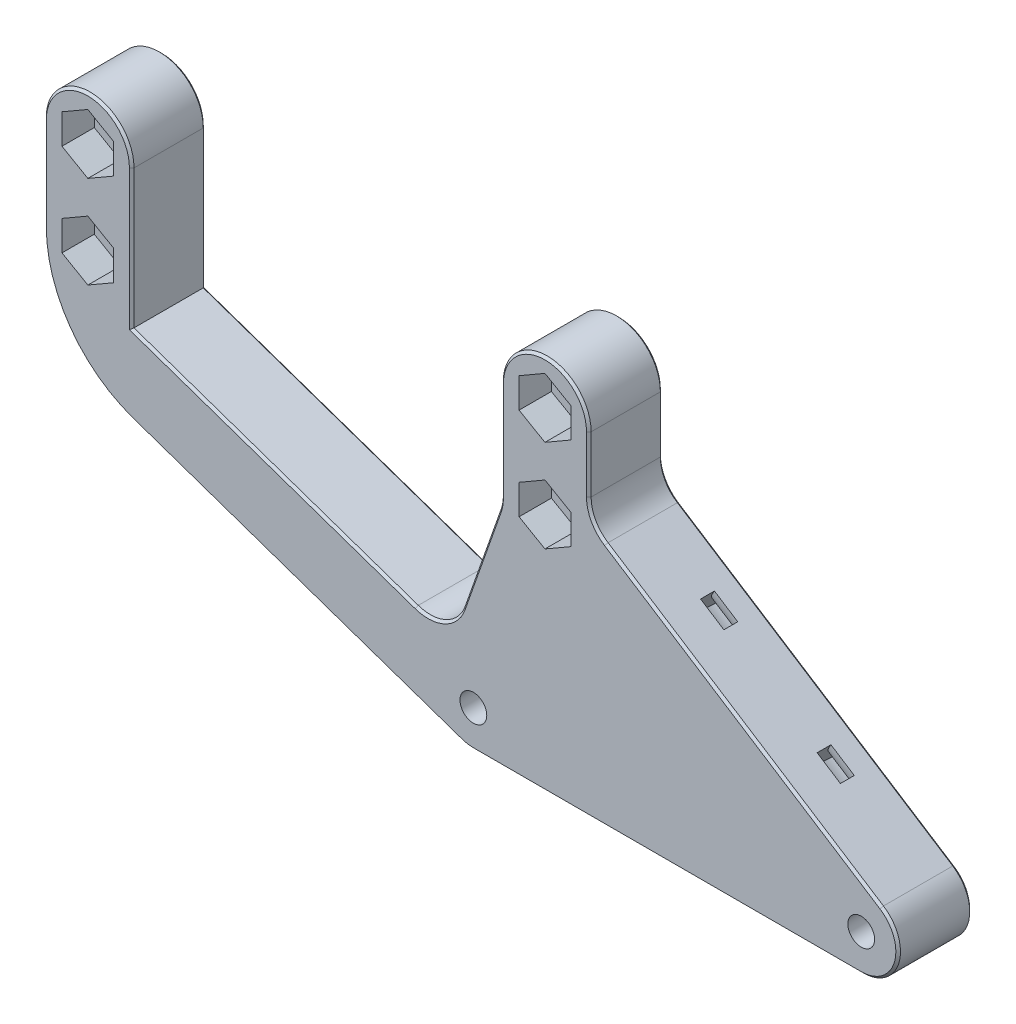
SolidWorks part; units mm, degrees
ref_plane "Płaszczyzna przednia" through (0, 0, 0) normal (0, 0, 1) x (1, 0, 0)
ref_plane "Płaszczyzna górna" through (0, 0, 0) normal (0, 1, 0) x (1, 0, 0)
ref_plane "Płaszczyzna prawa" through (0, 0, 0) normal (1, 0, 0) x (0, 0, -1)
sketch "Szkic1" plane through (0, 0, 0) normal (0, 0, 1) x (1, 0, 0)
  line L0 (0, 0) -> (7, -27) construction
  line L1 (7, -27) -> (49, -27) construction
  line L2 (0, 0) -> (-10, 0) construction
  line L3 (-34.75, 5) -> (14.75, 5) construction
  line L4 (-34.75, 5) -> (-34.75, -5) construction
  line L5 (-34.75, -5) -> (14.75, -5) construction
  line L6 (14.75, 5) -> (14.75, -5) construction
  line L7 (-34.75, 5) -> (14.75, -5) construction
  line L8 (-34.75, -5) -> (14.75, 5) construction
  line L9 (-34.75, 5) -> (-34.75, -5) construction
  line L10 (-30, 5) -> (-30, -5)
  line L11 (-39.5, 5) -> (-39.5, -5)
  line L12 (14.75, 5) -> (14.75, -5) construction
  line L13 (19.5, 5) -> (19.5, -5)
  line L14 (10, 5) -> (10, -5)
  line L15 (7, -27) -> (49, -27) construction
  line L16 (7, -27) -> (14.75, -5) construction
  line L17 (14.75, -5) -> (49, -27) construction
  line L18 (7, -23) -> (49, -23)
  line L19 (7, -31) -> (49, -31)
  line L20 (49, -27) -> (14.75, -5) construction
  line L21 (46.8382, -30.3655) -> (12.5882, -8.3655)
  line L22 (51.1618, -23.6345) -> (16.9118, -1.6345)
  line L23 (14.75, -5) -> (7, -27) construction
  line L24 (18.5228, -6.329) -> (10.7728, -28.329)
  line L25 (10.9772, -3.671) -> (3.2272, -25.671)
  line L26 (10, -5) -> (10, -6.4451)
  line L27 (7, -27) -> (-28.5677, -14.7258) construction
  line L28 (5.6951, -30.7812) -> (-29.8726, -18.5069)
  line L29 (8.3049, -23.2188) -> (-27.2628, -10.9446)
  line L30 (-30, -5) -> (-30, -10)
  line L31 (-27.2628, -10.9446) -> (-30, -10)
  circle A0 centre (7, -27) radius 1.45
  circle A1 centre (49, -27) radius 1.45
  circle A2 centre (14.75, -5) radius 1.55
  circle A3 centre (14.75, 5) radius 1.55
  circle A4 centre (-34.75, 5) radius 1.55
  circle A5 centre (-34.75, -5) radius 1.55
  arc A6 (-30, 5) -> (-39.5, 5) centre (-34.75, 5) ccw
  arc A7 (-39.5, -5) -> (-30, -5) centre (-34.75, -5) ccw
  arc A8 (19.5, 5) -> (10, 5) centre (14.75, 5) ccw
  arc A9 (10, -5) -> (19.5, -5) centre (14.75, -5) ccw
  arc A10 (7, -23) -> (7, -31) centre (7, -27) ccw
  arc A11 (49, -31) -> (49, -23) centre (49, -27) ccw
  arc A12 (46.8382, -30.3655) -> (51.1618, -23.6345) centre (49, -27) ccw
  arc A13 (16.9118, -1.6345) -> (12.5882, -8.3655) centre (14.75, -5) ccw
  arc A14 (18.5228, -6.329) -> (10.9772, -3.671) centre (14.75, -5) ccw
  arc A15 (3.2272, -25.671) -> (10.7728, -28.329) centre (7, -27) ccw
  arc A16 (5.6951, -30.7812) -> (8.3049, -23.2188) centre (7, -27) ccw
  arc A17 (-27.2628, -10.9446) -> (-29.8726, -18.5069) centre (-28.5677, -14.7258) ccw
  arc A18 (-39.5, -5) -> (-29.8726, -18.5069) centre (-25.2114, -5) ccw
  point P3 (-10, 0)
  point P16 (-34.75, 0)
  point P21 (14.75, 0)
  point P26 (28, -27)
  point P32 (31.875, -16)
  point P38 (10.875, -16)
  point P49 (-10.7839, -20.8629)
  dimension "D7" = 3.1
  dimension "D8" = 2.9
  dimension "D10" = 4
  dimension "D11" = 4
  dimension "D1" = 7
  dimension "D2" = 42
  dimension "D3" = 27
  dimension "D4" = 10
  dimension "D5" = 49.5
  dimension "D6" = 10
  dimension "D9" = 40
  dimension "D12" = 5
extrude "Dodanie-wyciągnięcie1" add sketch "Szkic1" along normal blind 8 contours A17 L29 L10 A6 L11 A7 A4 | L29 A17 A7 A5 | A7 A17 L28 A10 L25 L29 | A7 A18 A17 | A15 A16 L29 L18 A10 A0 | A10 L18 L29 L25 | A16 L24 L18 L29 | A15 L19 A12 L21 L18 L24 | A9 L25 L29 L18 L24 L21 | A11 L22 L13 A9 L24 L21 L18 | L21 A12 A11 L18 A1 | A9 L21 L24 | A13 L25 A9 L21 | A14 L24 A9 L13 L22 | L24 A14 A13 L21 A9 A2 | A13 L22 L13 A8 L14 A9 L25 A3 | A9 L26 L25
sketch "Szkic2" plane through (0, 0, 0) normal (0, 0, -1) x (-1, 0, 0)
  line L1 (-45.7668, -27) -> (-47.3834, -24.2)
  line L2 (-47.3834, -24.2) -> (-50.6166, -24.2)
  line L3 (-50.6166, -24.2) -> (-52.2332, -27)
  line L4 (-52.2332, -27) -> (-50.6166, -29.8)
  line L5 (-50.6166, -29.8) -> (-47.3834, -29.8)
  line L6 (-47.3834, -29.8) -> (-45.7668, -27)
  line L7 (-10.2332, -27) -> (-8.6166, -29.8)
  line L8 (-8.6166, -29.8) -> (-5.3834, -29.8)
  line L9 (-5.3834, -29.8) -> (-3.7668, -27)
  line L10 (-3.7668, -27) -> (-5.3834, -24.2)
  line L11 (-5.3834, -24.2) -> (-8.6166, -24.2)
  line L12 (-8.6166, -24.2) -> (-10.2332, -27)
  circle A0 centre (-49, -27) radius 2.8 construction
  circle A1 centre (-7, -27) radius 2.8 construction
  dimension "D1" = 5.6
extrude "Wytnij-wyciągnięcie1" cut sketch "Szkic2" against normal blind 3
fillet "Zaokrąglenie1" radius 4 3 edges at (10, -6.4451, 4) (4.5478, -21.9223, 4) (19.5, -3.297, 4)
sketch "Szkic3" plane through (0, 0, 8) normal (0, 0, 1) x (1, 0, 0)
  line L1 (-34.75, 1.7668) -> (-31.95, 3.3834)
  line L2 (-31.95, 3.3834) -> (-31.95, 6.6166)
  line L3 (-31.95, 6.6166) -> (-34.75, 8.2332)
  line L4 (-34.75, 8.2332) -> (-37.55, 6.6166)
  line L5 (-37.55, 6.6166) -> (-37.55, 3.3834)
  line L6 (-37.55, 3.3834) -> (-34.75, 1.7668)
  line L7 (-34.75, -8.2332) -> (-31.95, -6.6166)
  line L8 (-31.95, -6.6166) -> (-31.95, -3.3834)
  line L9 (-31.95, -3.3834) -> (-34.75, -1.7668)
  line L10 (-34.75, -1.7668) -> (-37.55, -3.3834)
  line L11 (-37.55, -3.3834) -> (-37.55, -6.6166)
  line L12 (-37.55, -6.6166) -> (-34.75, -8.2332)
  line L13 (14.75, 1.7668) -> (17.55, 3.3834)
  line L14 (17.55, 3.3834) -> (17.55, 6.6166)
  line L15 (17.55, 6.6166) -> (14.75, 8.2332)
  line L16 (14.75, 8.2332) -> (11.95, 6.6166)
  line L17 (11.95, 6.6166) -> (11.95, 3.3834)
  line L18 (11.95, 3.3834) -> (14.75, 1.7668)
  line L19 (14.75, -8.2332) -> (17.55, -6.6166)
  line L20 (17.55, -6.6166) -> (17.55, -3.3834)
  line L21 (17.55, -3.3834) -> (14.75, -1.7668)
  line L22 (14.75, -1.7668) -> (11.95, -3.3834)
  line L23 (11.95, -3.3834) -> (11.95, -6.6166)
  line L24 (11.95, -6.6166) -> (14.75, -8.2332)
  circle A0 centre (-34.75, 5) radius 2.8 construction
  circle A1 centre (-34.75, -5) radius 2.8 construction
  circle A2 centre (14.75, 5) radius 2.8 construction
  circle A3 centre (14.75, -5) radius 2.8 construction
  dimension "D1" = 5.6
extrude "Wytnij-wyciągnięcie2" cut sketch "Szkic3" against normal blind 3.5
chamfer "Sfazowanie1" distance 0.25 angle 45 34 edges at (-14.6046, -15.3129, 8) (-14.6046, -15.3129, 0) (3.8351, -20.4465, 8) (3.8351, -20.4465, 0) (7.8206, -12.6319, 8) (7.8206, -12.6319, 0) (9.9428, -6.4353, 8) (9.9428, -6.4353, 0) (10, -0.3806, 0) (10, -0.3806, 8) (14.75, 9.75, 0) (14.75, 9.75, 8) (19.5, 1.9439, 8) (19.5, 1.9439, 0) (19.9895, -3.0296, 8) (19.9895, -3.0296, 0) (36.25, -14.0561, 0) (36.25, -14.0561, 8) (52.8381, -28.1265, 0) (52.8381, -28.1265, 8) (28, -31, 0) (28, -31, 8) (6.3385, -30.9449, 0) (6.3385, -30.9449, 8) (-12.0887, -24.6441, 0) (-12.0887, -24.6441, 8) (-36.8468, -13.2934, 0) (-36.8468, -13.2934, 8) (-39.5, 0, 0) (-39.5, 0, 8) (-34.75, 9.75, 0) (-34.75, 9.75, 8) (-30, -2.5, 0) (-30, -2.5, 8)
sketch "Szkic4" plane through (0, 0, 0) normal (0, 0, -1) x (-1, 0, 0)
  line L0 (-40.7668, -25.5) -> (-40.7668, -28.5)
  line L1 (-40.7668, -28.5) -> (-37.0587, -27)
  line L2 (-37.0587, -27) -> (-40.7668, -25.5)
  line L3 (-45.7668, -27) -> (-40.7668, -27) construction
  dimension "D1" = 3
  dimension "D2" = 4
  dimension "D3" = 5
extrude "Wytnij-wyciągnięcie3" cut sketch "Szkic4" against normal blind 1
ref_plane "Płaszczyzna1" through (51.1618, -23.6345, 0.25) normal (-0.8414, 0.5404, 0) x (0, 0, 1)
ref_plane "Płaszczyzna2" through (42.748, -18.23, 0.25) normal (-0.8414, 0.5404, 0) x (0, 0, 1)
sketch "Szkic5" plane through (42.748, -18.23, 0.25) normal (-0.8414, 0.5404, 0) x (0, 0, 1)
  line L0 (7.5, 0) -> (0, 0) construction
  line L1 (-0.25, -0.25) -> (-0.25, -7.1552) construction
  line L2 (7.5, 0) -> (0, 0) construction
  line L3 (-0.25, -7.1875) -> (-0.25, -9.7117) construction
  line L4 (2.25, 0) -> (3.75, 0)
  line L5 (-0.25, -2.5) -> (-0.25, -4)
  arc A0 (2.25, 0) -> (-0.25, -2.5) centre (-0.25, 0) cw
  arc A1 (3.75, 0) -> (-0.25, -4) centre (-0.25, 0) cw
  dimension "D2" = 2.5
  dimension "D1" = 1.5
extrude "Wytnij-wyciągnięcie4" cut sketch "Szkic5" along normal blind 3
pattern_linear "Szyk liniowy1" count 2 spacing 15 along (-0.8414, 0.5404, 0) of "Wytnij-wyciągnięcie4"
